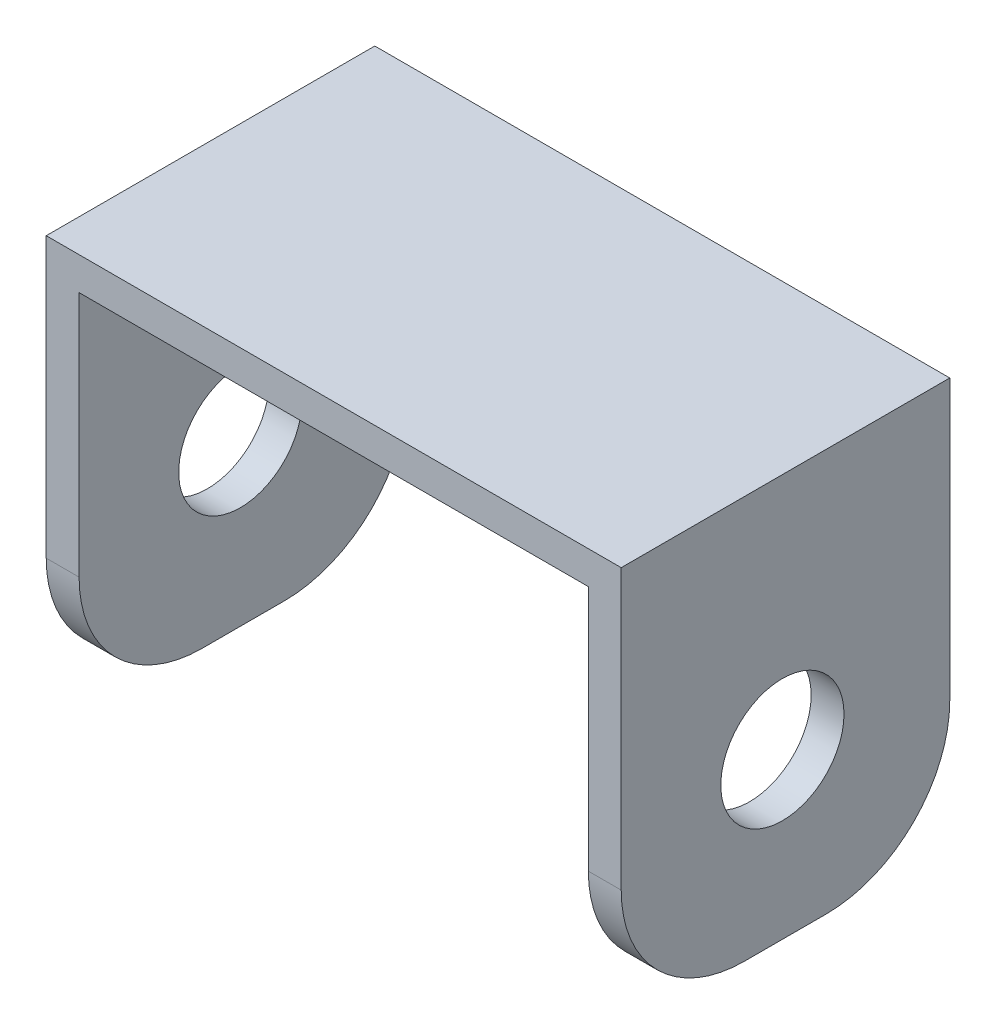
SolidWorks part; units mm, degrees
ref_plane "Front Plane" through (0, 0, 0) normal (0, 0, 1) x (1, 0, 0)
ref_plane "Top Plane" through (0, 0, 0) normal (0, 1, 0) x (1, 0, 0)
ref_plane "Right Plane" through (0, 0, 0) normal (1, 0, 0) x (0, 0, -1)
sketch "Sketch1" plane through (0, 0, 0) normal (0, 1, 0) x (1, 0, 0)
  line L1 (-14.2785, 10.3506) -> (21.2815, 10.3506)
  line L2 (-14.2785, 10.3506) -> (-14.2785, -9.9694)
  line L3 (-14.2785, -9.9694) -> (21.2815, -9.9694)
  line L4 (21.2815, 10.3506) -> (21.2815, -9.9694)
  dimension "D1" = 35.56
  dimension "D2" = 20.32
extrude "Boss-Extrude1" add sketch "Sketch1" along normal blind 2.032
sketch "Sketch2" plane through (0, 0, 0) normal (0, -1, 0) x (1, 0, 0)
  line L0 (21.2815, -10.3506) -> (-14.2785, -10.3506) construction
  line L1 (-14.2785, 9.9694) -> (-12.2465, 9.9694)
  line L2 (-14.2785, 9.9694) -> (-14.2785, -10.3506)
  line L3 (-14.2785, -10.3506) -> (-12.2465, -10.3506)
  line L4 (-12.2465, 9.9694) -> (-12.2465, -10.3506)
  line L5 (3.5015, 9.9694) -> (3.5015, -10.3506) construction
  line L6 (-14.2785, 9.9694) -> (21.2815, 9.9694) construction
  line L7 (21.2815, -10.3506) -> (19.2495, -10.3506)
  line L8 (19.2495, 9.9694) -> (19.2495, -10.3506)
  line L9 (21.2815, 9.9694) -> (19.2495, 9.9694)
  line L10 (21.2815, 9.9694) -> (21.2815, -10.3506)
  point P11 (0, 0)
  dimension "D1" = 2.032
extrude "Boss-Extrude2" add sketch "Sketch2" along normal blind 22.86
fillet "Fillet1" radius 7.62 4 edges at (20.2655, -22.86, -10.3506) (-13.2625, -22.86, -10.3506) (-13.2625, -22.86, 9.9694) (20.2655, -22.86, 9.9694)
sketch "Sketch3" plane through (21.2815, 0, 0) normal (1, 0, 0) x (0, 0, -1)
  line L0 (0, 13.6906) -> (0, -13.6906) construction
  line L1 (2.7306, -22.86) -> (-2.3494, -22.86) construction
  circle A0 centre (0, -12.7) radius 3.81
  dimension "D1" = 10.16
extrude "Cut-Extrude1" cut sketch "Sketch3" against normal blind 49.022
